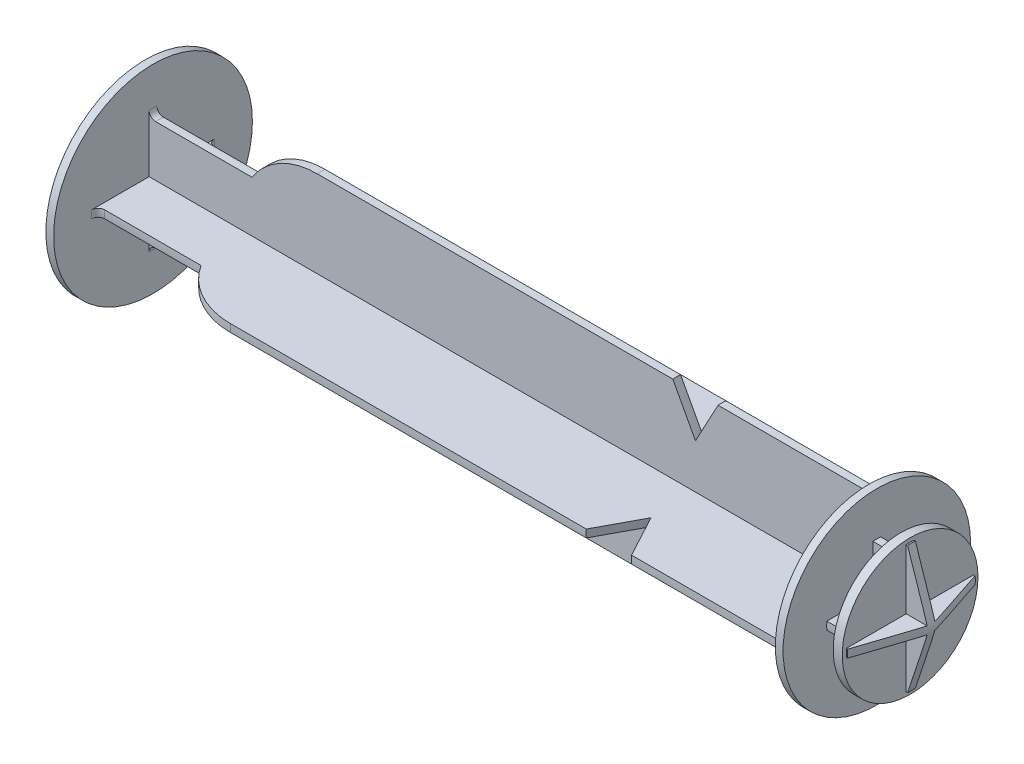
SolidWorks part; units mm, degrees
material "Polyethylene Cross-Linked"
ref_plane "Front Plane" through (0, 0, 0) normal (0, 0, 1) x (1, 0, 0)
ref_plane "Top Plane" through (0, 0, 0) normal (0, 1, 0) x (1, 0, 0)
ref_plane "Right Plane" through (0, 0, 0) normal (1, 0, 0) x (0, 0, -1)
sketch "Sketch1" plane through (0, 0, 0) normal (0, 0, 1) x (1, 0, 0)
  line L0 (121.8, 0) -> (-121.8, 0) construction
  line L1 (0, 0) -> (0, 15.375)
  line L2 (0, 15.375) -> (1.2, 15.375)
  line L3 (1.2, 15.375) -> (1.2, 9.5)
  line L4 (2.2, 8.5) -> (17.1129, 8.5)
  line L6 (27.2, 14) -> (82.2, 14)
  line L7 (82.2, 14) -> (85.7, 7.5)
  line L8 (85.7, 7.5) -> (89.2, 14)
  line L9 (89.2, 14) -> (111.95, 14)
  line L10 (111.95, 14) -> (111.95, 14.5)
  line L11 (111.95, 14.5) -> (113.15, 14.5)
  line L12 (113.15, 14.5) -> (113.15, 7.75)
  line L13 (113.15, 7.75) -> (116.9, 7.75)
  line L14 (116.9, 7.75) -> (116.9, 10.5)
  line L15 (116.9, 10.5) -> (118.3, 10.5)
  line L16 (118.3, 10.5) -> (121.8, 0)
  line L17 (0, 0) -> (121.8, 0)
  arc A0 (1.2, 9.5) -> (2.2, 8.5) centre (2.2, 9.5) ccw
  arc A1 (17.1129, 8.5) -> (27.2, 14) centre (27.2, 2) cw
  point P4 (0, 0)
  dimension "D14" = 1
  dimension "D15" = 12
  dimension "D1" = 1.2
  dimension "D2" = 110.75
  dimension "D3" = 30.75
  dimension "D4" = 17
  dimension "D5" = 84.5
  dimension "D6" = 15
  dimension "D7" = 7
  dimension "D8" = 28
  dimension "D9" = 29
  dimension "D10" = 15.5
  dimension "D11" = 21
  dimension "D12" = 121.8
  dimension "D13" = 3.75
  dimension "D17" = 26
  dimension "D18" = 3.5
revolve "Revolve1" add sketch "Sketch1" angle 360 about L0
sketch "Sketch2" plane through (1.2, 0, 0) normal (1, 0, 0) x (0, 0, -1)
  line L0 (17.7295, 0) -> (-17.7295, 0) construction
  line L1 (0, -17.5817) -> (0, 17.5817) construction
  line L2 (-0.6, 15.3633) -> (-0.6, 0.6)
  line L3 (-0.6, 0.6) -> (-15.3633, 0.6)
  line L4 (0.6, 0.6) -> (0.6, 15.3633)
  line L5 (15.3633, 0.6) -> (0.6, 0.6)
  line L6 (0.6, -0.6) -> (15.3633, -0.6)
  line L7 (0.6, -15.3633) -> (0.6, -0.6)
  line L8 (-0.6, -0.6) -> (-0.6, -15.3633)
  line L9 (-15.3633, -0.6) -> (-0.6, -0.6)
  circle A0 centre (0, 0) radius 15.375 construction
  arc A1 (-15.3633, 0.6) -> (-15.3633, -0.6) centre (0, 0) ccw
  arc A2 (0.6, 15.3633) -> (-0.6, 15.3633) centre (0, 0) ccw
  arc A3 (15.3633, -0.6) -> (15.3633, 0.6) centre (0, 0) ccw
  arc A4 (-0.6, -15.3633) -> (0.6, -15.3633) centre (0, 0) ccw
  point P5 (0, 0)
  point P9 (0, 0)
  point P27 (0, 0)
  dimension "D3" = 1.2
  dimension "D2" = 4
extrude "Cut-Extrude1" cut sketch "Sketch2" along normal up to surface (110.75 mm away) flip side to cut up to face at (111.95, 0, -14)
sketch "Sketch3" plane through (0, 0, 0) normal (-1, 0, 0) x (0, 0, 1)
  line L0 (2.75, -15.3669) -> (1.75, -15.3669)
  line L1 (0.5, -15.3669) -> (-0.5, -15.3669)
  line L2 (0.5, -15.3669) -> (0.5, 15.3669)
  line L3 (0.5, 15.3669) -> (-0.5, 15.3669)
  line L4 (-0.5, -15.3669) -> (-0.5, 15.3669)
  line L5 (0.5, -15.3669) -> (-0.5, 15.3669) construction
  line L6 (0.5, 15.3669) -> (-0.5, -15.3669) construction
  line L7 (1.75, -15.3669) -> (1.75, 15.3669)
  line L8 (2.75, 15.3669) -> (1.75, 15.3669)
  line L9 (2.75, -15.3669) -> (2.75, 15.3669)
  line L10 (5, -15.3669) -> (4, -15.3669)
  line L11 (4, -15.3669) -> (4, 15.3669)
  line L12 (5, 15.3669) -> (4, 15.3669)
  line L13 (5, -15.3669) -> (5, 15.3669)
  line L14 (7.25, -15.3669) -> (6.25, -15.3669)
  line L15 (6.25, -15.3669) -> (6.25, 15.3669)
  line L16 (7.25, 15.3669) -> (6.25, 15.3669)
  line L17 (7.25, -15.3669) -> (7.25, 15.3669)
  line L18 (9.5, -15.3669) -> (8.5, -15.3669)
  line L19 (8.5, -15.3669) -> (8.5, 15.3669)
  line L20 (9.5, 15.3669) -> (8.5, 15.3669)
  line L21 (9.5, -15.3669) -> (9.5, 15.3669)
  line L22 (11.75, -15.3669) -> (10.75, -15.3669)
  line L23 (10.75, -15.3669) -> (10.75, 15.3669)
  line L24 (11.75, 15.3669) -> (10.75, 15.3669)
  line L25 (11.75, -15.3669) -> (11.75, 15.3669)
  line L26 (14, -15.3669) -> (13, -15.3669)
  line L27 (13, -15.3669) -> (13, 15.3669)
  line L28 (14, 15.3669) -> (13, 15.3669)
  line L29 (14, -15.3669) -> (14, 15.3669)
  line L30 (-1.75, -15.3669) -> (-2.75, -15.3669)
  line L31 (-2.75, -15.3669) -> (-2.75, 15.3669)
  line L32 (-1.75, 15.3669) -> (-2.75, 15.3669)
  line L33 (-1.75, -15.3669) -> (-1.75, 15.3669)
  line L34 (-4, -15.3669) -> (-5, -15.3669)
  line L35 (-5, -15.3669) -> (-5, 15.3669)
  line L36 (-4, 15.3669) -> (-5, 15.3669)
  line L37 (-4, -15.3669) -> (-4, 15.3669)
  line L38 (-6.25, -15.3669) -> (-7.25, -15.3669)
  line L39 (-7.25, -15.3669) -> (-7.25, 15.3669)
  line L40 (-6.25, 15.3669) -> (-7.25, 15.3669)
  line L41 (-6.25, -15.3669) -> (-6.25, 15.3669)
  line L42 (-8.5, -15.3669) -> (-9.5, -15.3669)
  line L43 (-9.5, -15.3669) -> (-9.5, 15.3669)
  line L44 (-8.5, 15.3669) -> (-9.5, 15.3669)
  line L45 (-8.5, -15.3669) -> (-8.5, 15.3669)
  line L46 (-10.75, -15.3669) -> (-11.75, -15.3669)
  line L47 (-11.75, -15.3669) -> (-11.75, 15.3669)
  line L48 (-10.75, 15.3669) -> (-11.75, 15.3669)
  line L49 (-10.75, -15.3669) -> (-10.75, 15.3669)
  line L50 (-13, -15.3669) -> (-14, -15.3669)
  line L51 (-14, -15.3669) -> (-14, 15.3669)
  line L52 (-13, 15.3669) -> (-14, 15.3669)
  line L53 (-13, -15.3669) -> (-13, 15.3669)
  circle A0 centre (0, 0) radius 15.375 construction
  point P0 (0, 0)
  dimension "D1" = 1
  dimension "D3" = 2.25
  dimension "D2" = 7
  dimension "D4" = 7
extrude "Cut-Extrude2" [suppressed] cut sketch "Sketch3" against normal blind 0.2 flip side to cut
sketch "Sketch4" plane through (113.15, 0, 0) normal (1, 0, 0) x (0, 0, -1)
  line L8 (0.6, 0.6) -> (0.6, 15.3633)
  line L9 (-0.6, 15.3633) -> (-0.6, 0.6)
  line L10 (-0.6, 0.6) -> (-15.3633, 0.6)
  line L11 (-15.3633, -0.6) -> (-0.6, -0.6)
  line L12 (-0.6, -0.6) -> (-0.6, -15.3633)
  line L13 (0.6, -15.3633) -> (0.6, -0.6)
  line L14 (0.6, -0.6) -> (15.3633, -0.6)
  line L15 (15.3633, 0.6) -> (0.6, 0.6)
  line L16 (0.6, 0.6) -> (0.6, 15.3633)
  line L17 (-0.6, 15.3633) -> (-0.6, 0.6)
  line L18 (-0.6, 0.6) -> (-15.3633, 0.6)
  line L19 (-15.3633, -0.6) -> (-0.6, -0.6)
  line L20 (-0.6, -0.6) -> (-0.6, -15.3633)
  line L21 (0.6, -15.3633) -> (0.6, -0.6)
  line L22 (0.6, -0.6) -> (15.3633, -0.6)
  line L23 (15.3633, 0.6) -> (0.6, 0.6)
  arc A4 (0.6, 15.3633) -> (-0.6, 15.3633) centre (0, 0) ccw
  arc A5 (-15.3633, 0.6) -> (-15.3633, -0.6) centre (0, 0) ccw
  arc A6 (-0.6, -15.3633) -> (0.6, -15.3633) centre (0, 0) ccw
  arc A7 (15.3633, -0.6) -> (15.3633, 0.6) centre (0, 0) ccw
  arc A8 (0.6, 15.3633) -> (-0.6, 15.3633) centre (0, 0) ccw
  arc A9 (-15.3633, 0.6) -> (-15.3633, -0.6) centre (0, 0) ccw
  arc A10 (-0.6, -15.3633) -> (0.6, -15.3633) centre (0, 0) ccw
  arc A11 (15.3633, -0.6) -> (15.3633, 0.6) centre (0, 0) ccw
  dimension "D1" = 0
extrude "Cut-Extrude3" cut sketch "Sketch4" along normal up to surface (3.75 mm away) flip side to cut up to face at (116.9, 0, -7.75)
ref_plane "Plane1" through (121.8, 0, 0) normal (1, 0, 0) x (0, 0, -1)
sketch "Sketch5" plane through (121.8, 0, 0) normal (1, 0, 0) x (0, 0, -1)
  line L8 (0.6, 0.6) -> (0.6, 15.3633)
  line L9 (-0.6, 15.3633) -> (-0.6, 0.6)
  line L10 (-0.6, 0.6) -> (-15.3633, 0.6)
  line L11 (-15.3633, -0.6) -> (-0.6, -0.6)
  line L12 (-0.6, -0.6) -> (-0.6, -15.3633)
  line L13 (0.6, -15.3633) -> (0.6, -0.6)
  line L14 (0.6, -0.6) -> (15.3633, -0.6)
  line L15 (15.3633, 0.6) -> (0.6, 0.6)
  line L16 (0.6, 0.6) -> (0.6, 9.8568)
  line L17 (-0.6, 9.8568) -> (-0.6, 0.6)
  line L18 (-0.6, 0.6) -> (-9.8568, 0.6)
  line L19 (-9.8568, -0.6) -> (-0.6, -0.6)
  line L20 (-0.6, -0.6) -> (-0.6, -9.8568)
  line L21 (0.6, -9.8568) -> (0.6, -0.6)
  line L22 (0.6, -0.6) -> (9.8568, -0.6)
  line L23 (9.8568, 0.6) -> (0.6, 0.6)
  arc A0 (-9.8568, 0.6) -> (-9.8568, -0.6) centre (0, 0) ccw
  arc A1 (9.8568, -0.6) -> (9.8568, 0.6) centre (0, 0) ccw
  arc A2 (0.6, 9.8568) -> (-0.6, 9.8568) centre (0, 0) ccw
  arc A3 (-0.6, -9.8568) -> (0.6, -9.8568) centre (0, 0) ccw
  arc A4 (0.6, 15.3633) -> (-0.6, 15.3633) centre (0, 0) ccw
  arc A5 (-15.3633, 0.6) -> (-15.3633, -0.6) centre (0, 0) ccw
  arc A6 (-0.6, -15.3633) -> (0.6, -15.3633) centre (0, 0) ccw
  arc A7 (15.3633, -0.6) -> (15.3633, 0.6) centre (0, 0) ccw
  dimension "D2" = 19.75
  dimension "D1" = 0
extrude "Cut-Extrude4" cut sketch "Sketch5" against normal blind 3.5 flip side to cut
